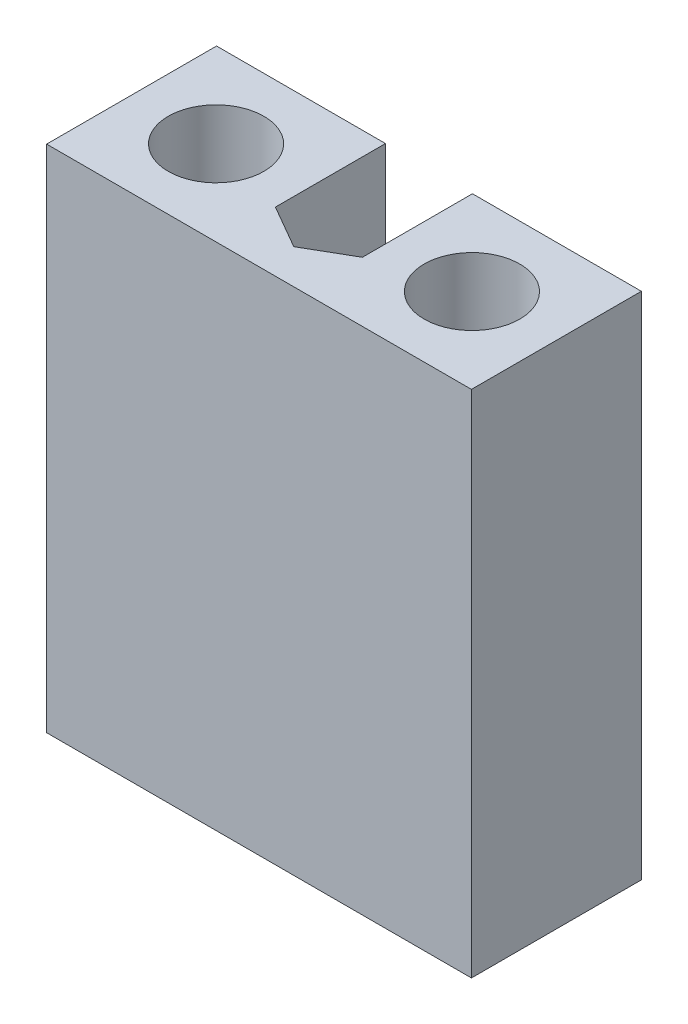
SolidWorks part; units mm, degrees
ref_plane "Front Plane" through (0, 0, 0) normal (0, 0, 1) x (1, 0, 0)
ref_plane "Top Plane" through (0, 0, 0) normal (0, 1, 0) x (1, 0, 0)
ref_plane "Right Plane" through (0, 0, 0) normal (1, 0, 0) x (0, 0, -1)
sketch "Sketch1" plane through (0, 0, 0) normal (0, 1, 0) x (1, 0, 0)
  line L0 (0, 7.5056) -> (0, 0) construction
  line L1 (0, -7.5056) -> (6.5, -3.7528)
  line L2 (6.5, -3.7528) -> (6.5, 3.7528)
  line L3 (6.5, 3.7528) -> (0, 7.5056) construction
  line L4 (0, 7.5056) -> (-6.5, 3.7528) construction
  line L5 (-6.5, 3.7528) -> (-6.5, -3.7528)
  line L6 (-6.5, -3.7528) -> (0, -7.5056)
  line L7 (-31.75, -12.7) -> (-31.75, 12.7)
  line L8 (-31.75, 12.7) -> (-6.5, 12.7)
  line L9 (-6.5, 12.7) -> (-6.5, 3.7528)
  line L10 (6.5, 3.7528) -> (6.5, 12.7)
  line L11 (6.5, 12.7) -> (31.75, 12.7)
  line L12 (31.75, 12.7) -> (31.75, -12.7)
  line L13 (31.75, -12.7) -> (-31.75, -12.7)
  line L14 (-31.75, 0) -> (0, 0) construction
  line L15 (0, 0) -> (31.75, 0) construction
  circle A0 centre (0, 0) radius 6.5 construction
  point P12 (-31.75, 0)
  dimension "D1" = 13
  dimension "D2" = 25.4
  dimension "D3" = 63.5
extrude "Boss-Extrude1" add sketch "Sketch1" along normal blind 76.2
hole_wizard "CBORE for 1/4 Binding Head Machine Screw1" positions "Sketch2" profile "Sketch3" counterbore size "1/4" standard "ANSI Inch" end condition through all
sketch "Sketch2" plane through (0, 76.2, 0) normal (0, 1, 0) x (1, 0, 0)
  line L0 (-19.125, 0) -> (0, 0) construction
  line L1 (0, 0) -> (19.125, 0) construction
  line L3 (-19.125, 0) -> (-19.125, 12.7) construction
  line L4 (-6.5, 12.7) -> (-31.75, 12.7) construction
  point P0 (-19.125, 0)
  point P2 (19.125, 0)
sketch "Sketch3" plane through (-19.125, 76.2, 0) normal (1, 0, 0) x (0, 0, 1)
  line L0 (0, 0) -> (0, 76.2)
  line L1 (0, 76.2) -> (3.3782, 76.2)
  line L3 (3.3782, 76.2) -> (3.3782, 54.991)
  line L4 (3.3782, 54.991) -> (7.1437, 54.991)
  line L5 (7.1437, 54.991) -> (7.1437, 0)
  line L7 (7.1437, 0) -> (0, 0)
  line L11 (0, -6.35) -> (0, 107.95) construction
  dimension "Thru Hole Dia." = 6.7564
  dimension "Thru Hole Depth" = 76.2
  dimension "C'Bore Dia." = 14.2875
  dimension "C'Bore Depth" = 54.991
